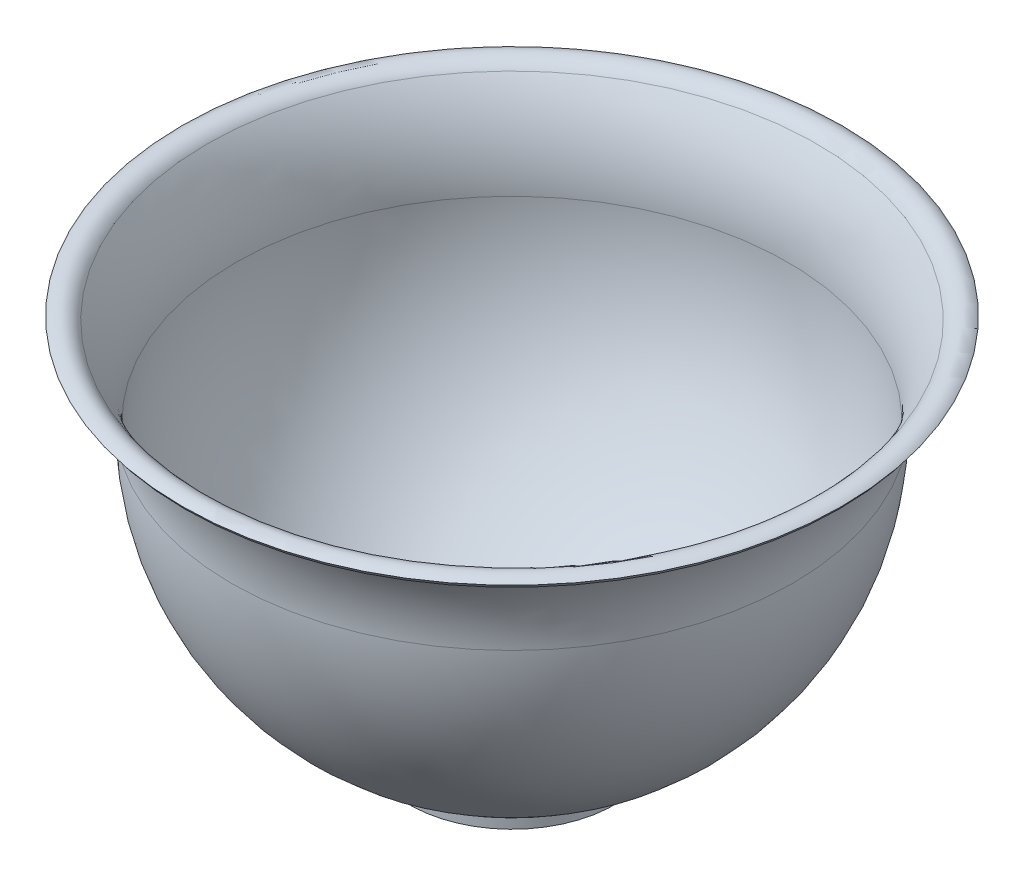
SolidWorks part; units mm, degrees
ref_plane "Front Plane" through (0, 0, 0) normal (0, 0, 1) x (1, 0, 0)
ref_plane "Top Plane" through (0, 0, 0) normal (0, 1, 0) x (1, 0, 0)
ref_plane "Right Plane" through (0, 0, 0) normal (1, 0, 0) x (0, 0, -1)
sketch "Sketch1" plane through (0, 0, 0) normal (0, 0, 1) x (1, 0, 0)
  line L0 (140.5853, 156.5307) -> (139.388, 154.9286)
  line L2 (0, 0) -> (0, -2)
  line L3 (43.7748, 6.3014) -> (43.7748, -2)
  line L4 (41.7748, 6.3014) -> (41.7748, -2)
  line L5 (41.7748, -2) -> (43.7748, -2)
  line L6 (41.7748, 6.3014) -> (43.7748, 6.3014)
  arc A0 (0, 0) -> (117.5664, 117.5835) centre (0, 117.5665) ccw
  arc A1 (117.5664, 117.5835) -> (130, 155) centre (180.0551, 117.5925) cw
  arc A2 (130, 155) -> (140.5853, 156.5307) centre (136.058, 150.4727) cw
  arc A3 (0, -2) -> (119.5664, 117.5838) centre (0, 117.5665) ccw
  arc A4 (119.5664, 117.5838) -> (131.6021, 153.8027) centre (180.0551, 117.5925) cw
  arc A5 (131.6021, 153.8027) -> (139.388, 154.9286) centre (136.058, 150.4727) cw
  point P15 (43.7748, 6.3014)
  dimension "D3" = 180.0551
  dimension "D1" = 117.5665
  dimension "D2" = 130
  dimension "D4" = 117.5925
  dimension "D5" = 180.0551
  dimension "D6" = 10.6954
  dimension "D7" = 6.058
  dimension "D9" = 43.7748
  dimension "D11" = 0
  dimension "D8" = 2
  dimension "D10" = 2
revolve "Revolve1" add sketch "Sketch1" angle 360 about L2
